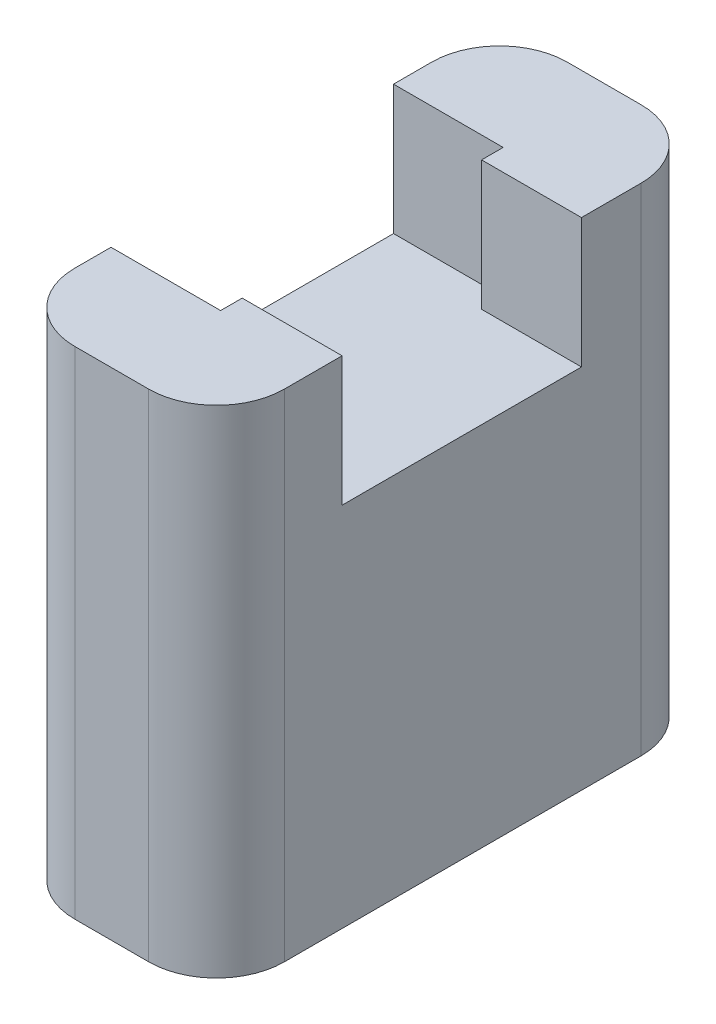
SolidWorks part; units mm, degrees
ref_plane "Alzado" through (0, 0, 0) normal (0, 0, 1) x (1, 0, 0)
ref_plane "Planta" through (0, 0, 0) normal (0, 1, 0) x (1, 0, 0)
ref_plane "Vista lateral" through (0, 0, 0) normal (1, 0, 0) x (0, 0, -1)
sketch "Croquis1" plane through (0, 0, 0) normal (0, 1, 0) x (1, 0, 0)
  line L0 (35.1175, -10.7686) -> (17.8519, -10.7686)
  line L1 (17.8519, -3.7972) -> (35.1175, -3.7972)
  line L2 (17.8519, -10.7686) -> (17.8519, -15.5115)
  line L3 (14.709, -18.6543) -> (11.2805, -18.6543)
  line L4 (8.1376, -15.5115) -> (8.1376, 1.0364)
  line L5 (11.2805, 4.1793) -> (14.709, 4.1793)
  line L6 (17.8519, 1.0364) -> (17.8519, -3.7972)
  arc A0 (14.709, -18.6543) -> (17.8519, -15.5115) centre (14.709, -15.5115) ccw
  arc A1 (8.1376, -15.5115) -> (11.2805, -18.6543) centre (11.2805, -15.5115) ccw
  arc A2 (11.2805, 4.1793) -> (8.1376, 1.0364) centre (11.2805, 1.0364) ccw
  arc A3 (17.8519, 1.0364) -> (14.709, 4.1793) centre (14.709, 1.0364) ccw
  arc A4 (35.1175, -10.7686) -> (35.1175, -3.7972) centre (38.1627, -7.2829) ccw
  circle A5 centre (38.1627, -7.2829) radius 2.4
  dimension "D1" = 4.8
extrude "Saliente-Extruir1" add sketch "Croquis1" along normal blind 3
sketch "Croquis2" plane through (0, 3, 0) normal (0, 1, 0) x (1, 0, 0)
  line L0 (13.2204, -1.7329) -> (4.9451, -1.7329) construction
  line L1 (13.2204, -1.7329) -> (17.8519, -1.7329)
  line L2 (17.8519, -3.7972) -> (17.8519, 1.0364) construction
  line L3 (13.2204, -12.8329) -> (17.8519, -12.8329)
  line L5 (38.1627, -7.2829) -> (2.3035, -7.2829) construction
  line L6 (7.1204, -0.7329) -> (13.2204, -0.7329)
  line L7 (7.1204, -0.7329) -> (7.1204, -13.8329)
  line L8 (7.1204, -13.8329) -> (13.2204, -13.8329)
  line L9 (13.2204, -0.7329) -> (13.2204, -13.8329)
  circle A4 centre (38.1627, -7.2829) radius 2.4 construction
  circle A5 centre (38.1627, -7.2829) radius 2.4
  line M7 (17.8519, -3.7972) -> (17.8519, 1.0364)
  arc M8 (17.8519, 1.0364) -> (14.709, 4.1793) centre (14.709, 1.0364) ccw
  line M9 (14.709, 4.1793) -> (11.2805, 4.1793)
  arc M10 (11.2805, 4.1793) -> (8.1376, 1.0364) centre (11.2805, 1.0364) ccw
  line M11 (8.1376, 1.0364) -> (8.1376, -15.5115)
  arc M12 (8.1376, -15.5115) -> (11.2805, -18.6543) centre (11.2805, -15.5115) ccw
  line M13 (11.2805, -18.6543) -> (14.709, -18.6543)
  arc M14 (14.709, -18.6543) -> (17.8519, -15.5115) centre (14.709, -15.5115) ccw
  line M15 (17.8519, -15.5115) -> (17.8519, -10.7686)
  dimension "D3" = 1
  dimension "D1" = 6.1
  dimension "D2" = 6.55
  dimension "D4" = 13.1
extrude "Saliente-Extruir2" add sketch "Croquis2" along normal blind 6 contours L6 L9 L1 M7 M8 M9 M10 M11 | L3 L9 L8 M11 M12 M13 M14 M15
sketch "Croquis3" plane through (0, 3, 0) normal (0, 1, 0) x (1, 0, 0)
  line L2 (17.8519, -3.7972) -> (17.8519, -10.7686)
extrude "Cortar-Extruir4" cut sketch "Croquis3" against normal blind 3 and the other way through all
sketch "Croquis4" plane through (0, 0, 0) normal (0, -1, 0) x (1, 0, 0)
  line L0 (17.8519, 15.5115) -> (17.8519, -1.0364) construction
  line L1 (14.709, -4.1793) -> (11.2805, -4.1793) construction
  line L2 (8.1376, -1.0364) -> (8.1376, 15.5115) construction
  line L3 (11.2805, 18.6543) -> (14.709, 18.6543) construction
  line L4 (17.8519, 15.5115) -> (17.8519, -1.0364)
  line L5 (14.709, -4.1793) -> (11.2805, -4.1793)
  line L6 (8.1376, -1.0364) -> (8.1376, 15.5115)
  line L7 (11.2805, 18.6543) -> (14.709, 18.6543)
  arc A0 (14.709, -4.1793) -> (17.8519, -1.0364) centre (14.709, -1.0364) ccw construction
  arc A1 (8.1376, -1.0364) -> (11.2805, -4.1793) centre (11.2805, -1.0364) ccw construction
  arc A2 (11.2805, 18.6543) -> (8.1376, 15.5115) centre (11.2805, 15.5115) ccw construction
  arc A3 (17.8519, 15.5115) -> (14.709, 18.6543) centre (14.709, 15.5115) ccw construction
  arc A4 (14.709, -4.1793) -> (17.8519, -1.0364) centre (14.709, -1.0364) ccw
  arc A5 (8.1376, -1.0364) -> (11.2805, -4.1793) centre (11.2805, -1.0364) ccw
  arc A6 (11.2805, 18.6543) -> (8.1376, 15.5115) centre (11.2805, 15.5115) ccw
  arc A7 (17.8519, 15.5115) -> (14.709, 18.6543) centre (14.709, 15.5115) ccw
extrude "Saliente-Extruir3" add sketch "Croquis4" along normal blind 14
